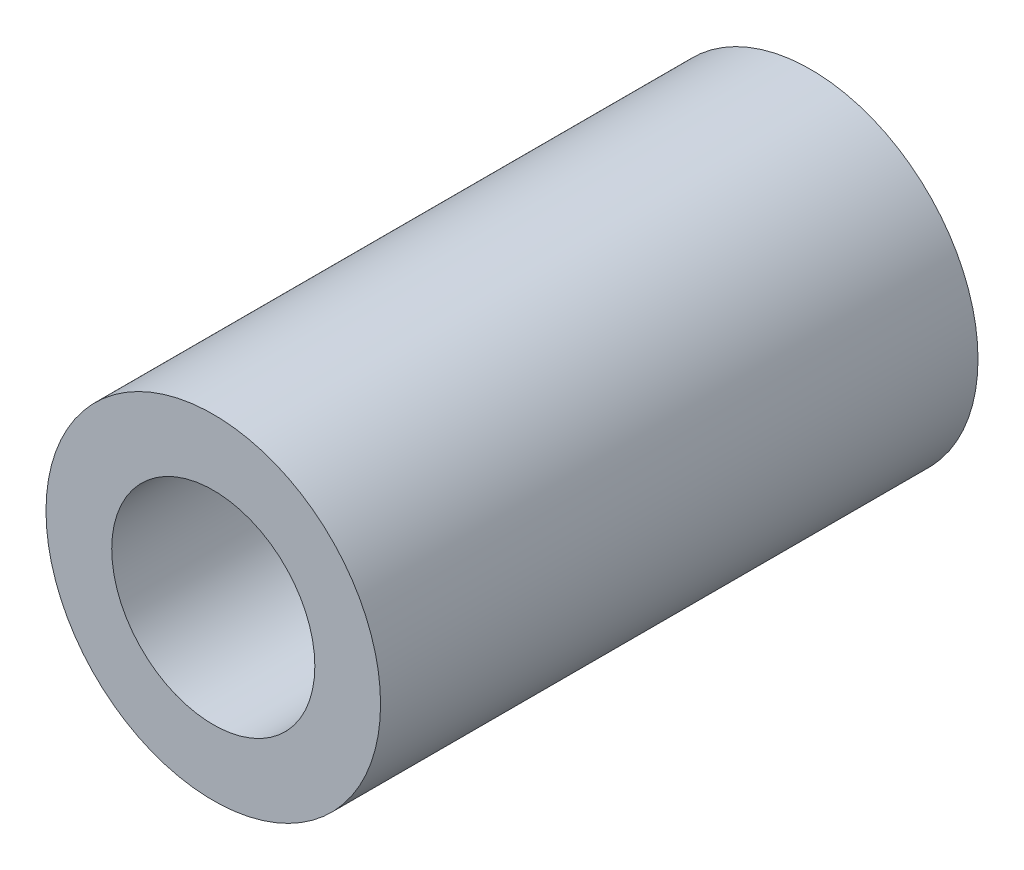
SolidWorks part; units mm, degrees
ref_plane "Ön Düzlem" through (0, 0, 0) normal (0, 0, 1) x (1, 0, 0)
ref_plane "Üst Düzlem" through (0, 0, 0) normal (0, 1, 0) x (1, 0, 0)
ref_plane "Sağ Düzlem" through (0, 0, 0) normal (1, 0, 0) x (0, 0, -1)
sketch "Sketch1" plane through (0, 0, 0) normal (0, 0, 1) x (1, 0, 0)
  circle A0 centre (0, 0) radius 7
  circle A1 centre (0, 0) radius 4.25
  dimension "D1" = 14
  dimension "D2" = 8.5
extrude "Boss-Extrude1" add sketch "Sketch1" along normal blind 25
